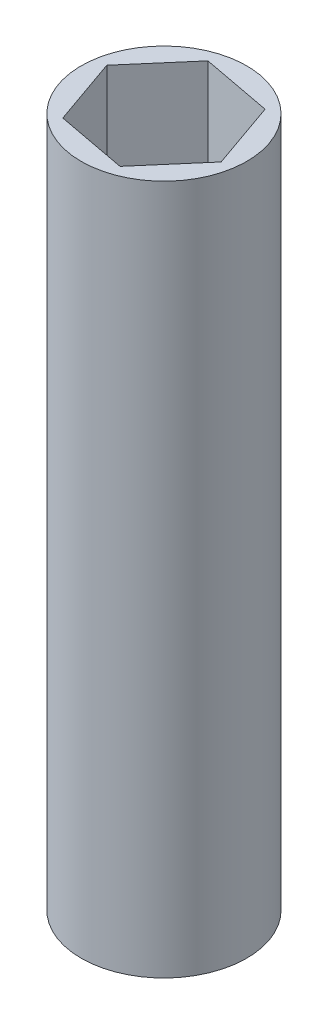
SolidWorks part; units mm, degrees
ref_plane "前视基准面" through (0, 0, 0) normal (0, 0, 1) x (1, 0, 0)
ref_plane "上视基准面" through (0, 0, 0) normal (0, 1, 0) x (1, 0, 0)
ref_plane "右视基准面" through (0, 0, 0) normal (1, 0, 0) x (0, 0, -1)
other "Configuration Table"
sketch "草图1" plane through (0, 0, 0) normal (0, 1, 0) x (1, 0, 0)
  line L1 (24.7629, -1.7701) -> (13.9144, 20.5603)
  line L2 (13.9144, 20.5603) -> (-10.8485, 22.3303)
  line L3 (-10.8485, 22.3303) -> (-24.7629, 1.7701)
  line L4 (-24.7629, 1.7701) -> (-13.9144, -20.5603)
  line L5 (-13.9144, -20.5603) -> (10.8485, -22.3303)
  line L6 (10.8485, -22.3303) -> (24.7629, -1.7701)
  circle A0 centre (0, 0) radius 30
  circle A1 centre (0, 0) radius 21.5 construction
  dimension "D1" = 60
  dimension "D2" = 43
extrude "凸台-拉伸1" add sketch "草图1" along normal blind 250 contours A0
sketch "草图3" plane through (0, 250, 0) normal (0, 1, 0) x (1, 0, 0)
  line L1 (25.5314, -4.8112) -> (16.9323, 19.7052)
  line L2 (16.9323, 19.7052) -> (-8.5991, 24.5164)
  line L3 (-8.5991, 24.5164) -> (-25.5314, 4.8112)
  line L4 (-25.5314, 4.8112) -> (-16.9323, -19.7052)
  line L5 (-16.9323, -19.7052) -> (8.5991, -24.5164)
  line L6 (8.5991, -24.5164) -> (25.5314, -4.8112)
  circle A0 centre (0, 0) radius 22.5 construction
  dimension "D1" = 45
extrude "切除-拉伸1" cut sketch "草图3" against normal through all
